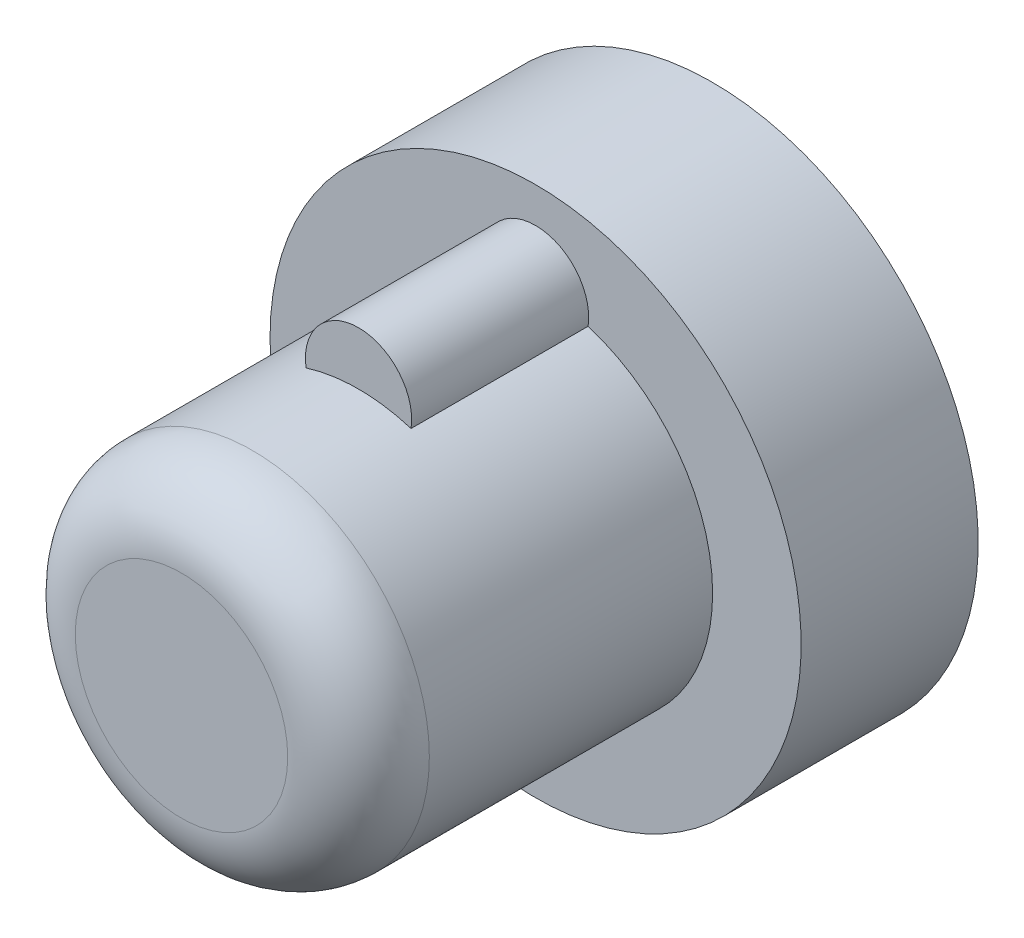
SolidWorks part; units mm, degrees
ref_plane "前视基准面" through (0, 0, 0) normal (0, 0, 1) x (1, 0, 0)
ref_plane "上视基准面" through (0, 0, 0) normal (0, 1, 0) x (1, 0, 0)
ref_plane "右视基准面" through (0, 0, 0) normal (1, 0, 0) x (0, 0, -1)
sketch "草图1" plane through (0, 0, 0) normal (0, 0, 1) x (1, 0, 0)
  circle A0 centre (0, 0) radius 5
  dimension "D1" = 10
extrude "凸台-拉伸1" add sketch "草图1" along normal blind 10
sketch "草图2" plane through (0, 0, 0) normal (0, 0, -1) x (-1, 0, 0)
  line L0 (-1000, 0) -> (49000, 0) construction
  line L1 (0, -1000) -> (0, 49000) construction
  circle A0 centre (0, 0) radius 7.5
  dimension "D1" = 15
extrude "凸台-拉伸2" add sketch "草图2" along normal blind 5 contours A0
fillet "圆角1" radius 2 1 edges at (5, 0, 10)
sketch "草图5" plane through (0, 0, 0) normal (0, 0, 1) x (1, 0, 0)
  line L0 (0, -1000) -> (0, 49000) construction
  circle A0 centre (0, 5) radius 1.5
  point P2 (0, 4.2409)
  point P3 (0, 7.9885)
  point P5 (0, 10)
  dimension "D1" = 3
  dimension "D2" = 5
extrude "凸台-拉伸4" add sketch "草图5" along normal blind 5
